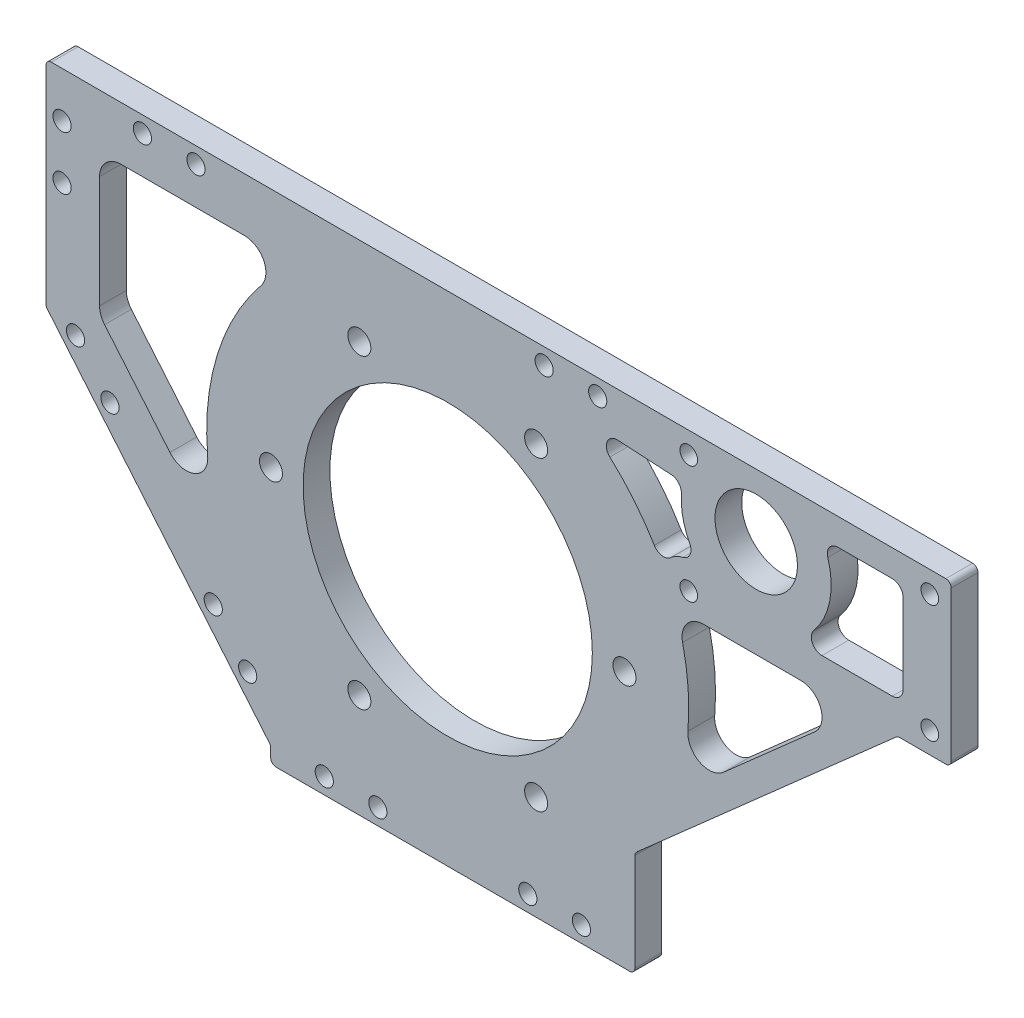
SolidWorks part; units mm, degrees
material "黑板"
ref_plane "前视基准面" through (0, 0, 0) normal (0, 0, 1) x (1, 0, 0)
ref_plane "上视基准面" through (0, 0, 0) normal (0, 1, 0) x (1, 0, 0)
ref_plane "右视基准面" through (0, 0, 0) normal (1, 0, 0) x (0, 0, -1)
sketch "草图1" plane through (0, 0, 0) normal (0, 0, 1) x (1, 0, 0)
  line L1 (-75, 45) -> (75, 45)
  line L2 (-75, 45) -> (-75, -45)
  line L3 (-75, -45) -> (75, -45)
  line L4 (75, 45) -> (75, -45)
  line L5 (-75, 45) -> (75, -45) construction
  line L6 (-75, -45) -> (75, 45) construction
  point P0 (0, 0)
  dimension "D1" = 90
  dimension "D2" = 150
extrude "凸台-拉伸1" add sketch "草图1" along normal blind 5 contours L2 L3 L4 L1
sketch "草图2" plane through (0, 0, 5) normal (0, 0, 1) x (1, 0, 0)
  line L0 (0, 0) -> (57.5903, 33.2498)
  line L1 (57.5903, 33.2498) -> (128.899, -36.8577)
  line L2 (128.899, -36.8577) -> (1.0407, -115.9519)
  line L3 (0, 0) -> (98.0863, -55.9187)
  circle A0 centre (0, 0) radius 18.5 construction
  circle A1 centre (0, 0) radius 40 construction
  dimension "D1" = 37
  dimension "D2" = 80
  dimension "D3" = 30
  dimension "D4" = 66.4995
  dimension "D5" = 100
  dimension "D6" = 112.9063
  dimension "D7" = 36.2318
  dimension "D8" = 114.1133
  dimension "D9" = 150.3451
sketch "草图3" plane through (0, 0, 5) normal (0, 0, 1) x (1, 0, 0)
  circle A0 centre (0, 0) radius 27
  dimension "D1" = 54
extrude "切除-拉伸1" cut sketch "草图3" against normal blind 5
sketch "草图4" plane through (0, 0, 5) normal (0, 0, 1) x (1, 0, 0)
  line L0 (0, 0) -> (16.5, 28.5788) construction
  circle A1 centre (16.5, 28.5788) radius 2.15
  circle A2 centre (0, 0) radius 33 construction
  circle A3 centre (33, 0) radius 2.15
  circle A4 centre (16.5, -28.5788) radius 2.15
  circle A5 centre (-16.5, -28.5788) radius 2.15
  circle A6 centre (-33, 0) radius 2.15
  circle A7 centre (-16.5, 28.5788) radius 2.15
  point P18 (0, 0)
  dimension "D1" = 66
  dimension "D3" = 4.3
  dimension "D2" = 30
  dimension "D4" = 6
extrude "切除-拉伸2" cut sketch "草图4" against normal through all
sketch "草图5" plane through (0, 0, 5) normal (0, 0, 1) x (1, 0, 0)
  circle A0 centre (57.5903, 33.2498) radius 7.7
  dimension "D1" = 15.4
extrude "切除-拉伸3" cut sketch "草图5" against normal through all contours A0
chamfer "倒角1" distance 40 angle 45 1 edges at (75, -45, 2.5)
chamfer "倒角3" distance 50 angle 40 1 edges at (-75, -45, 2.5)
sketch "草图6" plane through (0, 0, 0) normal (0, 0, -1) x (-1, 0, 0)
  line L0 (-39.0373, -40.9627) -> (-35, -40.9627)
  line L1 (-75, -5) -> (-35, -45) construction
  line L2 (-35, -40.9627) -> (-35, -45)
  line L3 (-39.0373, -40.9627) -> (-35, -45)
  line L4 (0, 0) -> (0, -60.797) construction
  line L5 (36.4327, -40.9627) -> (33.045, -40.9627)
  line L6 (33.045, -40.9627) -> (33.045, -45)
  line L7 (36.4327, -40.9627) -> (33.045, -45)
  line L8 (33.045, -45) -> (75, 5) construction
  line L9 (33.045, -45) -> (-35, -45) construction
  dimension "D1" = 60
extrude "切除-拉伸4" cut sketch "草图6" against normal through all
sketch "草图7" plane through (0, 0, 5) normal (0, 0, 1) x (1, 0, 0)
  line L0 (75, 45) -> (94, 45)
  line L2 (94, 45) -> (94, 15)
  line L3 (94, 15) -> (75, 15)
  line L4 (75, 45) -> (75, -5) construction
  line L5 (75, 15) -> (75, 45)
  dimension "D1" = 19
  dimension "D2" = 30
extrude "凸台-拉伸2" add sketch "草图7" against normal through all
chamfer "倒角2" distance 10 angle 45 1 edges at (75, 15, 2.5)
sketch "草图8" plane through (0, 0, 5) normal (0, 0, 1) x (1, 0, 0)
  line L0 (45, 41) -> (90, 41) construction
  line L1 (90, 41) -> (90, 19) construction
  line L2 (94, 15) -> (94, 45) construction
  line L3 (-75, 45) -> (94, 45) construction
  line L4 (45, 41) -> (45, 19) construction
  line L5 (45, 19) -> (90, 19) construction
  circle A0 centre (90, 19) radius 1.65
  circle A1 centre (90, 41) radius 1.65
  circle A2 centre (45, 41) radius 1.65
  circle A3 centre (45, 19) radius 1.65
  dimension "D5" = 3.3
  dimension "D1" = 45
  dimension "D2" = 22
  dimension "D3" = 4
  dimension "D4" = 4
extrude "切除-拉伸5" cut sketch "草图8" against normal through all
sketch "草图10" plane through (0, 0, 5) normal (0, 0, 1) x (1, 0, 0)
  circle A1 centre (-37.3485, -35.2041) radius 1.7
  circle A3 centre (-43.7764, -27.5436) radius 1.7
  circle A8 centre (-72, 36.5) radius 1.7
  circle A9 centre (-72, 26.5) radius 1.7
  circle A10 centre (-69.4879, 3.0981) radius 1.7
  circle A11 centre (-63.0601, -4.5623) radius 1.7
  dimension "D1" = 3.4
extrude "切除-拉伸6" cut sketch "草图10" against normal through all
sketch "草图11" plane through (0, 0, 5) normal (0, 0, 1) x (1, 0, 0)
  circle A2 centre (-47, 42) radius 1.7
  circle A3 centre (-57, 42) radius 1.7
  circle A5 centre (18, 42) radius 1.7
  circle A7 centre (28, 42) radius 1.7
  dimension "D1" = 3.4
extrude "切除-拉伸7" cut sketch "草图11" against normal through all
sketch "草图13" plane through (0, 0, 5) normal (0, 0, 1) x (1, 0, 0)
  line L0 (-65, 35) -> (-65, 8.6397)
  line L1 (-65, 8.6397) -> (-39.1851, -22.1253)
  line L2 (-65, 35) -> (-28.2843, 35)
  line L3 (-75, 5) -> (-36.4327, -40.9627) construction
  line L4 (-49.0575, -10.3599) -> (-56.7179, -16.7877) construction
  line L5 (34.955, -28.3399) -> (34.955, -45)
  line L6 (-65, 35) -> (-75, 35) construction
  line L7 (-75, 45) -> (-75, 5) construction
  line L8 (-65, 35) -> (-65, 45) construction
  line L9 (-75, 45) -> (94, 45) construction
  line L10 (34.955, -45) -> (35, -45)
  line L11 (35, -45) -> (85, -3.3848)
  line L12 (85, -3.3848) -> (85, 15)
  line L13 (85, 15) -> (42.4264, 15)
  line L14 (-33.045, -45) -> (35, -45) construction
  line L15 (-33.045, -40.9627) -> (-33.045, -45) construction
  arc A0 (-28.2843, 35) -> (-39.1851, -22.1253) centre (0, 0) ccw
  arc A1 (42.4264, 15) -> (-28.2843, 35) centre (0, 0) ccw construction
  arc A2 (-39.1851, -22.1253) -> (34.955, -28.3399) centre (0, 0) ccw construction
  arc A3 (34.955, -28.3399) -> (42.4264, 15) centre (0, 0) ccw
  dimension "D1" = 10
  dimension "D2" = 68
extrude "切除-拉伸9" cut sketch "草图13" against normal through all
sketch "草图14" plane through (0, 0, 5) normal (0, 0, 1) x (1, 0, 0)
  line L0 (34.955, -28.3399) -> (84, 15)
  line L1 (42.4264, 15) -> (94, 15) construction
  line L2 (94, 15) -> (94, 45) construction
  dimension "D1" = 10
extrude "拉伸-薄壁1" add sketch "草图14" against normal through all thin contours L0 thin type one direction reverse wall 5
sketch "草图15" plane through (0, 0, 5) normal (0, 0, 1) x (1, 0, 0)
  line L0 (64.3684, 21) -> (85, 21)
  line L1 (85, 21) -> (85, 40)
  line L2 (85, 40) -> (69.8554, 40)
  line L3 (-75, 45) -> (94, 45) construction
  line L4 (42.4264, 15) -> (76.4492, 15) construction
  line L5 (28, 42) -> (45, 41) construction
  line L6 (25.403, 37.1441) -> (43.8747, 36.0576)
  arc A0 (64.3684, 21) -> (69.8554, 40) centre (57.5903, 33.2498) ccw
  circle A1 centre (57.5903, 33.2498) radius 7.7 construction
  circle A2 centre (90, 41) radius 1.65 construction
  arc A3 (43.8747, 36.0576) -> (48.3205, 22.7582) centre (57.5903, 33.2498) ccw
  arc A4 (40.158, 20.306) -> (25.403, 37.1441) centre (0, 0) ccw
  arc A5 (48.3205, 22.7582) -> (40.158, 20.306) centre (45, 19) ccw
  arc A6 (42.3928, -15.0948) -> (42.4264, 15) centre (0, 0) ccw construction
  arc A7 (69.8554, 40) -> (43.8747, 36.0576) centre (57.5903, 33.2498) ccw construction
  arc A8 (48.3205, 22.7582) -> (64.3684, 21) centre (57.5903, 33.2498) ccw construction
  arc A9 (42.5592, 14.6191) -> (48.3205, 22.7582) centre (45, 19) ccw construction
  arc A10 (42.5592, 14.6191) -> (40.158, 20.306) centre (0, 0) ccw construction
  arc A11 (40.158, 20.306) -> (42.5592, 14.6191) centre (45, 19) ccw construction
  arc A12 (25.403, 37.1441) -> (42.5592, 14.6191) centre (0, 0) ccw construction
  dimension "D1" = 5
  dimension "D3" = 28
  dimension "D4" = 5
  dimension "D2" = 5
  dimension "5" = 6
extrude "切除-拉伸10" cut sketch "草图15" against normal through all
fillet "圆角1" radius 2 8 edges at (48.3205, 22.7582, 2.5) (40.158, 20.306, 2.5) (64.3684, 21, 2.5) (85, 21, 2.5) (85, 40, 2.5) (69.8554, 40, 2.5) (25.403, 37.1441, 2.5) (43.8747, 36.0576, 2.5)
fillet "圆角2" radius 4 7 edges at (-28.2843, 35, 2.5) (-39.1851, -22.1253, 2.5) (-65, 8.6397, 2.5) (-65, 35, 2.5) (42.3928, -15.0948, 2.5) (76.4492, 15, 2.5) (42.4264, 15, 2.5)
sketch "草图16" plane through (0, -45, 0) normal (0, -1, 0) x (1, 0, 0)
  line L4 (34.955, 5) -> (-33.045, 5)
  line L5 (-33.045, 5) -> (-33.045, 0)
  line L6 (-33.045, 0) -> (34.955, 0)
  line L7 (34.955, 0) -> (34.955, 5)
  line L8 (34.955, 5) -> (-33.045, 5)
  line L9 (-33.045, 5) -> (-33.045, 0)
  line L10 (-33.045, 0) -> (34.955, 0)
  line L12 (34.955, 0) -> (34.955, 5)
  dimension "D1" = 0
extrude "凸台-拉伸3" add sketch "草图16" along normal blind 3
sketch "草图17" plane through (0, 0, 5) normal (0, 0, 1) x (1, 0, 0)
  line L0 (-36.4327, -40.9627) -> (-33.045, -45)
  line L1 (-33.045, -40.9627) -> (-33.045, -48) construction
  line L2 (-33.045, -45) -> (-33.045, -40.9627)
  line L3 (-33.045, -40.9627) -> (-36.4327, -40.9627)
  line L4 (-75, 5) -> (-36.4327, -40.9627) construction
extrude "凸台-拉伸4" add sketch "草图17" against normal through all
fillet "圆角3" radius 1 9 edges at (84, 15, 2.5) (-75, 45, 2.5) (-75, 5, 2.5) (94, 45, 2.5) (94, 15, 2.5) (-33.045, -48, 2.5) (34.955, -48, 2.5) (-33.045, -45, 2.5) (34.955, -28.3399, 2.5)
sketch "草图18" plane through (0, 0, 5) normal (0, 0, 1) x (1, 0, 0)
  circle A4 centre (24.955, -45) radius 1.7
  circle A5 centre (14.955, -45) radius 1.7
  circle A6 centre (-13.045, -45) radius 1.7
  circle A7 centre (-23.045, -45) radius 1.7
  dimension "D1" = 3.4
extrude "切除-拉伸11" cut sketch "草图18" against normal through all
sketch "草图19" [suppressed] plane through (0, 0, 5) normal (0, 0, 1) x (1, 0, 0)
  line L0 (83.7663, 45) -> (94, 39.9969)
  line L1 (45, 19) -> (90, 19) construction
  line L2 (45, 19) -> (45, 37.5) construction
  line L3 (45, 37.5) -> (90, 37.5) construction
  line L4 (90, 19) -> (90, 37.5) construction
  line L5 (-74, 45) -> (93, 45) construction
  line L6 (94, 16) -> (94, 44) construction
  line L7 (94, 39.9969) -> (94, 45)
  line L8 (94, 45) -> (83.7663, 45)
  line L9 (90, 37.5) -> (91.7568, 41.0935) construction
  line L10 (90, 37.5) -> (94, 37.5) construction
  line L11 (90, 19) -> (45, 41) construction
  circle A0 centre (90, 37.5) radius 1.65
  circle A1 centre (90, 19) radius 1.65 construction
  dimension "D1" = 18.5
  dimension "D2" = 45
sketch "草图20" [suppressed] plane through (0, 0, 5) normal (0, 0, 1) x (1, 0, 0)
  circle A0 centre (90, 41) radius 1.65 construction
  circle A1 centre (90, 41) radius 1.65
extrude "凸台-拉伸5" [suppressed] add sketch "草图20" against normal through all
extrude "切除-拉伸12" [suppressed] cut sketch "草图19" against normal through all
fillet "圆角4" [suppressed] radius 1
